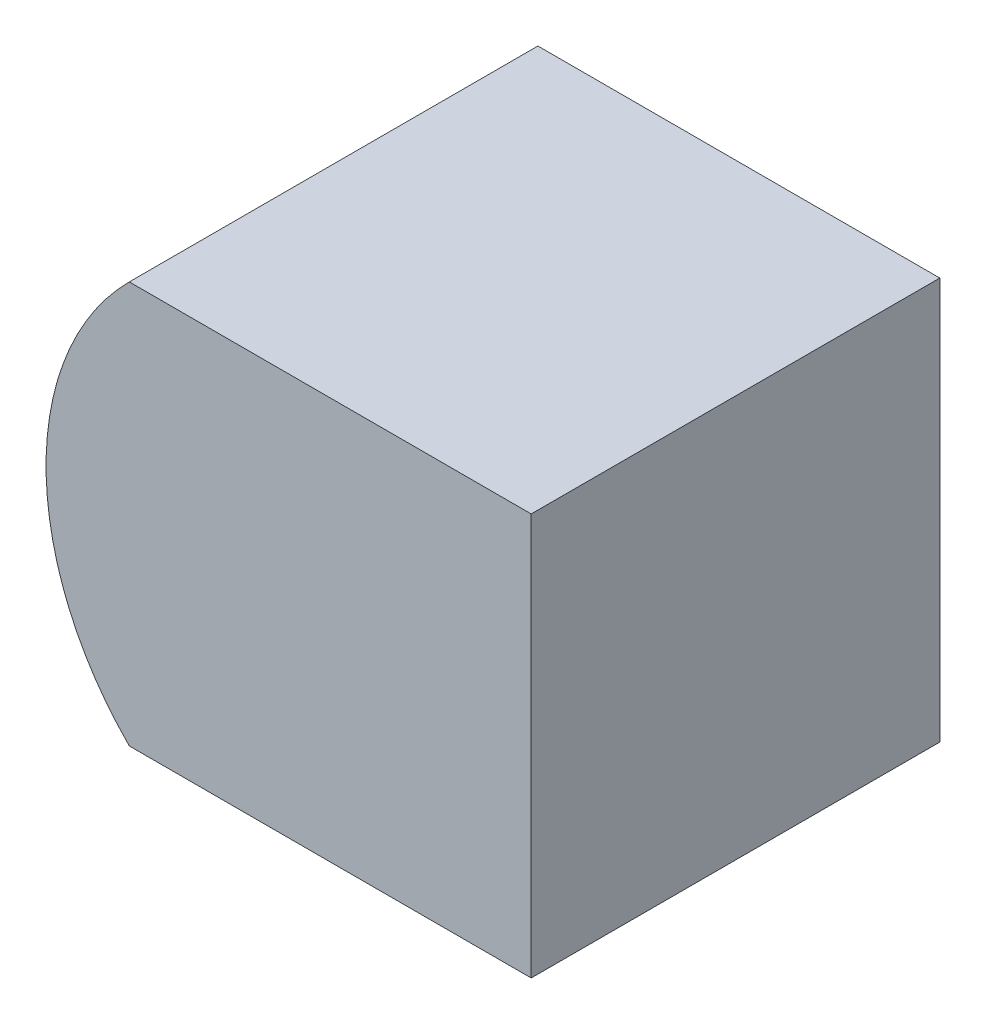
SolidWorks part; units mm, degrees
ref_plane "Front Plane" through (0, 0, 0) normal (0, 0, 1) x (1, 0, 0)
ref_plane "Top Plane" through (0, 0, 0) normal (0, 1, 0) x (1, 0, 0)
ref_plane "Right Plane" through (0, 0, 0) normal (1, 0, 0) x (0, 0, -1)
sketch "Sketch1" plane through (0, 0, 0) normal (0, 0, 1) x (1, 0, 0)
  line L1 (-30, 30) -> (30, 30)
  line L3 (-30, -30) -> (30, -30)
  line L4 (30, 30) -> (30, -30)
  line L5 (-30, 30) -> (30, -30) construction
  line L6 (-30, -30) -> (30, 30) construction
  arc A1 (-30, 30) -> (-30, -30) centre (0, 0) ccw
  point P0 (0, 0)
  point P8 (0, 0)
  dimension "D1" = 60
  dimension "D2" = 60
extrude "Boss-Extrude1" add sketch "Sketch1" along normal blind 61
